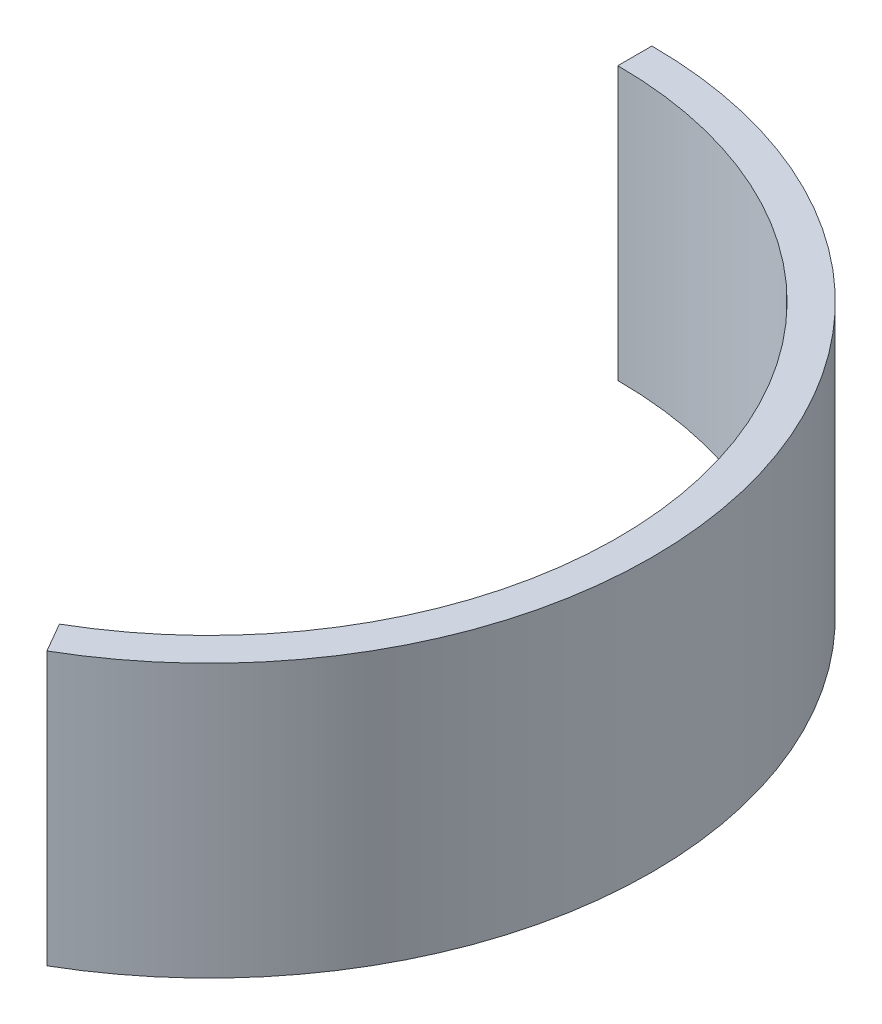
SolidWorks part; units mm, degrees
ref_plane "Front Plane" through (0, 0, 0) normal (0, 0, 1) x (1, 0, 0)
ref_plane "Top Plane" through (0, 0, 0) normal (0, 1, 0) x (1, 0, 0)
ref_plane "Right Plane" through (0, 0, 0) normal (1, 0, 0) x (0, 0, -1)
sketch "Sketch1" plane through (0, 0, 0) normal (0, 1, 0) x (1, 0, 0)
  line L0 (19.0386, -71.0529) -> (20.6261, -73.8025)
  line L1 (0, 0) -> (-28.2364, 0) construction
  line L2 (0, 0) -> (0, 3.175)
  line L3 (19.0386, -71.0529) -> (11.1292, -75.6194) construction
  arc A0 (0, 0) -> (19.0386, -71.0529) centre (0, -38.0771) cw
  arc A1 (0, 3.175) -> (20.6261, -73.8025) centre (0, -38.0771) cw
  dimension "D3" = 41.2521
  dimension "D1" = 3.175
  dimension "D2" = 150
extrude "Boss-Extrude1" add sketch "Sketch1" along normal blind 25.4
